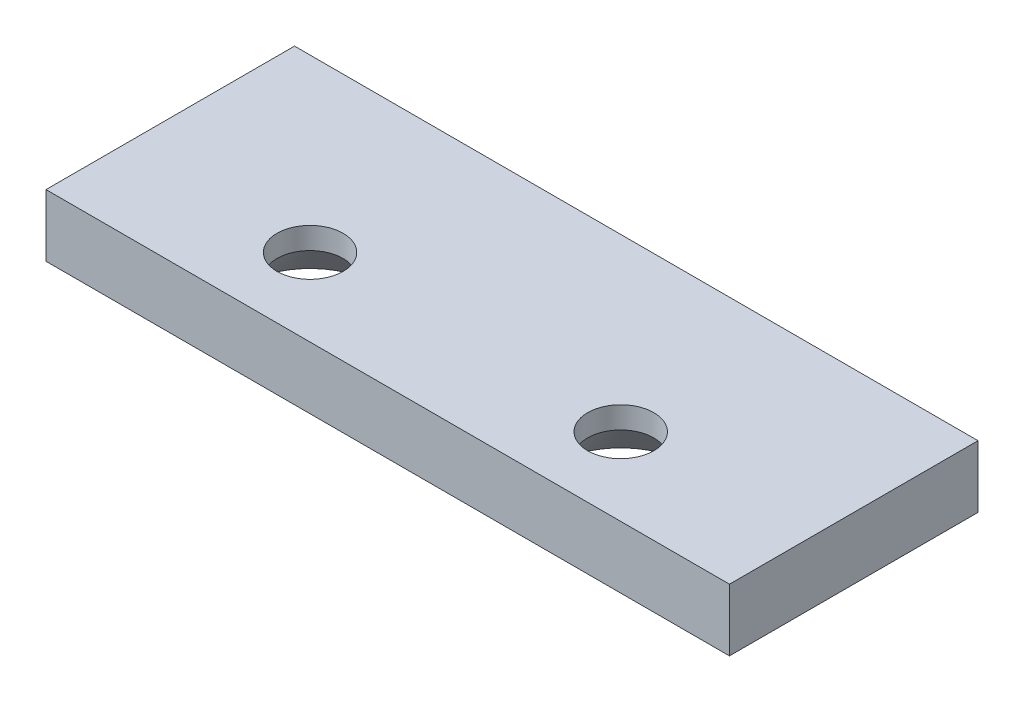
SolidWorks part; units mm, degrees
material "6061 Alloy"
ref_plane "Front Plane" through (0, 0, 0) normal (0, 0, 1) x (1, 0, 0)
ref_plane "Top Plane" through (0, 0, 0) normal (0, 1, 0) x (1, 0, 0)
ref_plane "Right Plane" through (0, 0, 0) normal (1, 0, 0) x (0, 0, -1)
sketch "Sketch1" plane through (0, 0, 0) normal (0, 1, 0) x (1, 0, 0)
  line L1 (34.925, -12.7) -> (-34.925, -12.7)
  line L2 (34.925, -12.7) -> (34.925, 12.7)
  line L3 (34.925, 12.7) -> (-34.925, 12.7)
  line L4 (-34.925, -12.7) -> (-34.925, 12.7)
  line L5 (34.925, -12.7) -> (-34.925, 12.7) construction
  line L6 (34.925, 12.7) -> (-34.925, -12.7) construction
  point P0 (0, 0)
  dimension "D1" = 69.85
  dimension "D2" = 25.4
extrude "Boss-Extrude1" add sketch "Sketch1" along normal blind 6.35
hole_wizard "CSK for 1/4 Flat Head Machine Screw1" positions "Sketch2" profile "Sketch3" countersink size "1/4" standard "ANSI Inch"
sketch "Sketch2" plane through (0, 0, 0) normal (0, -1, 0) x (-1, 0, 0)
  line L0 (34.925, -12.7) -> (-34.925, -12.7) construction
  line L1 (34.925, 12.7) -> (34.925, -12.7) construction
  line L2 (-34.925, -12.7) -> (-34.925, 12.7) construction
  point P0 (15.875, -4.7625)
  point P2 (-15.875, -4.7625)
  dimension "D1" = 7.9375
  dimension "D2" = 7.9375
  dimension "D3" = 19.05
  dimension "D4" = 19.05
sketch "Sketch3" plane through (-15.875, 0, 4.7625) normal (1, 0, 0) x (0, 0, -1)
  line L0 (0, 0) -> (0, 17.2698)
  line L1 (0, 17.2698) -> (3.3782, 15.24)
  line L2 (3.3782, 15.24) -> (3.3782, 4.1199)
  line L3 (3.3782, 4.1199) -> (6.9596, 0)
  line L5 (6.9596, 0) -> (0, 0)
  line L6 (-3.3782, 4.1199) -> (-6.9596, 0) construction
  line L10 (0, 17.2698) -> (-3.3782, 15.24) construction
  line L11 (0, -6.35) -> (0, 107.95) construction
  dimension "Hole Dia." = 6.7564
  dimension "Hole Depth" = 15.24
  dimension "Near C'Sink Dia." = 13.9192
  dimension "Near C'Sink Angle" = 82
  dimension "Drill Angle" = 118
